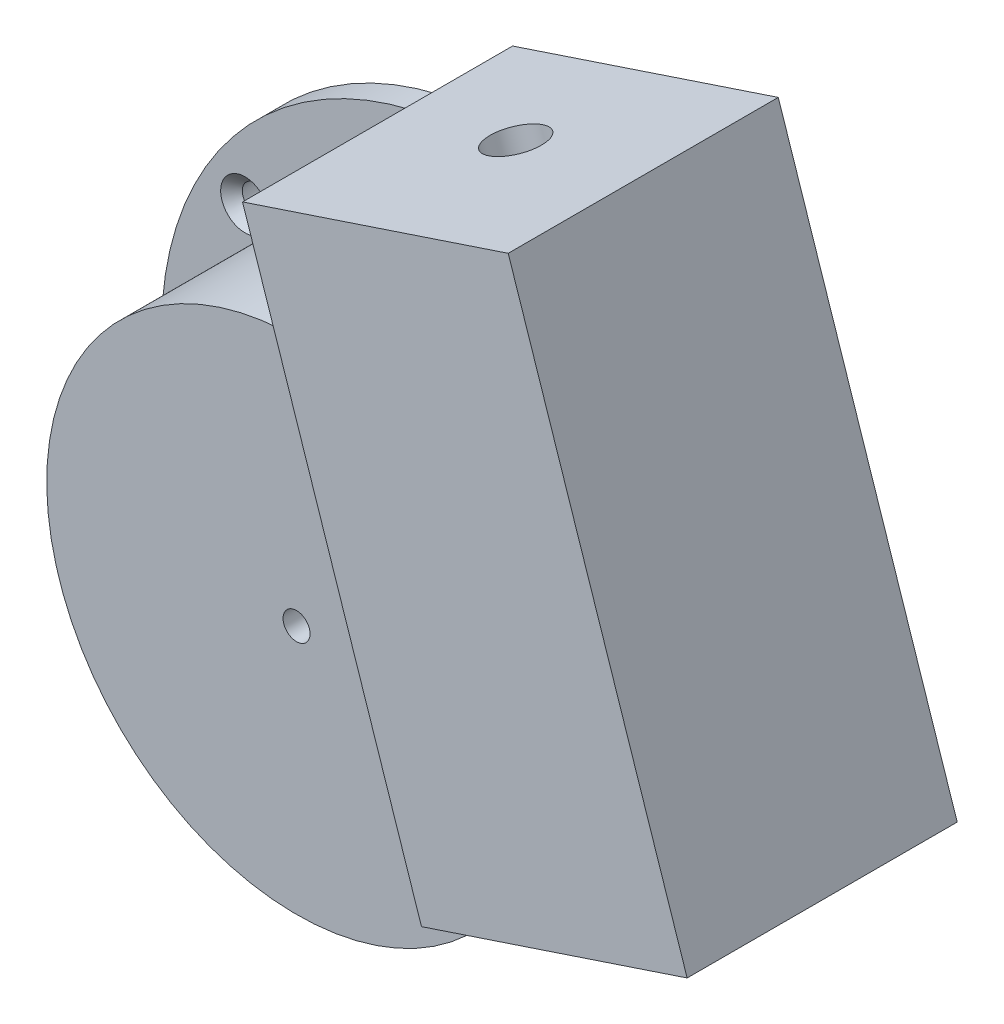
SolidWorks part; units mm, degrees
ref_plane "Piano frontale" through (0, 0, 0) normal (0, 0, 1) x (1, 0, 0)
ref_plane "Piano superiore" through (0, 0, 0) normal (0, 1, 0) x (1, 0, 0)
ref_plane "Piano destro" through (0, 0, 0) normal (1, 0, 0) x (0, 0, -1)
sketch "Schizzo1" plane through (0, 0, 0) normal (0, 0, 1) x (1, 0, 0)
  line L0 (1.7522, 23.936) -> (0, 29.2054)
  line L1 (0, 29.2054) -> (19.6753, 35.7477)
  line L2 (19.6753, 35.7477) -> (32.9272, -4.106)
  line L3 (32.9272, -4.106) -> (22.8076, -7.471)
  line L6 (4.2368, 16.4636) -> (13.2519, -10.6483)
  arc A0 (4.2368, 16.4636) -> (13.2519, -10.6483) centre (0, 0) ccw
  arc A1 (1.7522, 23.936) -> (22.8076, -7.471) centre (0, 0) ccw
  dimension "D1" = 34
  dimension "D2" = 48
extrude "Estrusione-Estrusione1" add sketch "Schizzo1" along normal blind 2
sketch "Schizzo3" plane through (0, 0, 2) normal (0, 0, 1) x (1, 0, 0)
  line L0 (13.2519, -10.6483) -> (15.6616, -9.8471)
  line L1 (22.8076, -7.471) -> (32.9272, -4.106) construction
  line L2 (4.2368, 16.4636) -> (3.6828, 18.1297)
  line L3 (0, 29.2054) -> (1.7522, 23.936) construction
  arc A1 (3.6828, 18.1297) -> (15.6616, -9.8471) centre (0, 0) ccw
  arc A2 (4.2368, 16.4636) -> (13.2519, -10.6483) centre (0, 0) ccw
  arc A3 (4.2368, 16.4636) -> (13.2519, -10.6483) centre (0, 0) ccw construction
  dimension "D1" = 37
extrude "Estrusione-Estrusione3" add sketch "Schizzo3" along normal blind 12
sketch "Schizzo5" plane through (0, 0, 2) normal (0, 0, 1) x (1, 0, 0)
  line L0 (4.2368, 16.4636) -> (9.2007, 7.8737)
  line L1 (9.2007, 7.8737) -> (2.5289, 27.9386)
  line L2 (2.5289, 27.9386) -> (18.4085, 33.2188)
  line L3 (18.4085, 33.2188) -> (30.3983, -2.8392)
  line L4 (30.3983, -2.8392) -> (12.6208, -8.7505)
  line L5 (13.2519, -10.6483) -> (12.6208, -8.7505)
  line L6 (13.2519, -10.6483) -> (32.9272, -4.106)
  line L7 (32.9272, -4.106) -> (19.6753, 35.7477)
  line L8 (19.6753, 35.7477) -> (0, 29.2054)
  line L9 (0, 29.2054) -> (4.2368, 16.4636)
  line L10 (13.2519, -10.6483) -> (4.2368, 16.4636) construction
  dimension "D1" = 2
  dimension "D2" = 2
  dimension "D3" = 2
  dimension "D4" = 2
extrude "Estrusione-Estrusione4" add sketch "Schizzo5" along normal blind 12
sketch "Schizzo7" plane through (0, 0, 2) normal (0, 0, 1) x (1, 0, 0)
  circle A0 centre (0, 0) radius 17
extrude "Taglio-Estrusione1" cut sketch "Schizzo7" against normal mid plane 24
sketch "Schizzo10" plane through (0, 0, 14) normal (0, 0, 1) x (1, 0, 0)
  line L0 (18.4085, 33.2188) -> (30.3983, -2.8392) construction
  line L1 (30.3983, -2.8392) -> (14.5187, -8.1194)
  line L2 (30.3983, -2.8392) -> (18.4085, 33.2188)
  line L3 (18.4085, 33.2188) -> (2.5289, 27.9386)
  line L4 (14.5187, -8.1194) -> (2.5289, 27.9386)
  line L5 (32.9272, -4.106) -> (13.2519, -10.6483)
  line L6 (32.9272, -4.106) -> (19.6753, 35.7477)
  line L7 (19.6753, 35.7477) -> (0, 29.2054)
  line L8 (13.2519, -10.6483) -> (0, 29.2054)
extrude "Estrusione-Estrusione5" add sketch "Schizzo10" along normal blind 4
sketch "Schizzo11" plane through (0, 0, 18) normal (0, 0, 1) x (1, 0, 0)
  line L0 (13.2519, -10.6483) -> (15.6616, -9.8471) construction
  line L1 (32.9272, -4.106) -> (13.2519, -10.6483)
  line L2 (32.9272, -4.106) -> (19.6753, 35.7477)
  line L3 (19.6753, 35.7477) -> (0, 29.2054)
  line L4 (13.2519, -10.6483) -> (0, 29.2054)
  arc A0 (4.2368, 16.4636) -> (13.2519, -10.6483) centre (0, 0) ccw construction
extrude "Estrusione-Estrusione6" add sketch "Schizzo11" along normal blind 2
sketch "Schizzo12" plane through (0, 0, 14) normal (0, 0, 1) x (1, 0, 0)
  circle A0 centre (0, 0) radius 18.5
extrude "Estrusione-Estrusione7" add sketch "Schizzo12" along normal blind 2
sketch "Schizzo13" plane through (0, 0, 16) normal (0, 0, 1) x (1, 0, 0)
  circle A0 centre (0, 0) radius 1
  dimension "D1" = 2
extrude "Taglio-Estrusione2" cut sketch "Schizzo13" against normal blind 2
sketch "Schizzo14" plane through (-8.7444, 26.2978, 0) normal (-0.3155, 0.9489, 0) x (0.9489, 0.3155, 0)
  line L0 (9.2151, -16) -> (9.2151, -18) construction
  line L1 (9.2151, -20) -> (9.2151, 0) construction
  line L2 (9.2151, -18) -> (28.6731, 0) construction
  line L3 (29.9496, 0) -> (9.2151, 0) construction
  line L5 (9.2151, 0) -> (29.9496, -18) construction
  line L6 (29.9496, -20) -> (29.9496, 0) construction
  circle A0 centre (18.9441, -9) radius 2
  dimension "D2" = 4
  dimension "D1" = 2
extrude "Taglio-Estrusione3" cut sketch "Schizzo14" against normal blind 2
sketch "Schizzo15" plane through (0, 0, 2) normal (0, 0, 1) x (1, 0, 0)
  line L0 (12.7002, 20.3643) -> (-12.7002, -20.3643) construction
  line L1 (-20.3643, 12.7002) -> (20.3643, -12.7002) construction
  line L2 (0, 0) -> (0.8165, 23.9861) construction
  circle A0 centre (0, 0) radius 21
  arc A1 (1.7522, 23.936) -> (22.8076, -7.471) centre (0, 0) ccw construction
  dimension "D3" = 30
  dimension "D1" = 42
  dimension "D2" = 24
hole_wizard "Foro svasato per Vite M1.6-1" positions "Schizzo3D1" profile "Schizzo16" countersink size "M1.6" standard "ISO" end condition through all
sketch3d "Schizzo3D1"
  line L0 (0, 0, 2) -> (0.8165, 23.9861, 2) construction
  line L1 (-20.3643, 12.7002, 2) -> (20.3643, -12.7002, 2) construction
  line L2 (12.7002, 20.3643, 2) -> (-12.7002, -20.3643, 2) construction
  circle A0 centre (0, 0, 2) radius 21 construction
  point P0 (0.7144, 20.9878, 2)
  point P6 (0, 0, 23)
  point P7 (-17.8188, 11.1126, 2)
  point P11 (-11.1126, -17.8188, 2)
  point P15 (17.8188, -11.1126, 2)
sketch "Schizzo16" plane through (0.7144, 20.9878, 2) normal (1, 0, 0) x (0, -1, 0)
  line L0 (0, 0) -> (0, 2)
  line L1 (0, 2) -> (1, 2)
  line L2 (1, 2) -> (1, 0.8)
  line L3 (1, 0.8) -> (1.8, 0)
  line L5 (1.8, 0) -> (0, 0)
  line L6 (-1, 0.8) -> (-1.8, 0) construction
  line L11 (0, -6.35) -> (0, 107.95) construction
  dimension "Thru Hole Dia." = 2
  dimension "Thru Hole Depth" = 2
  dimension "Near C'Sink Dia." = 3.6
  dimension "Near C'Sink Angle" = 90
